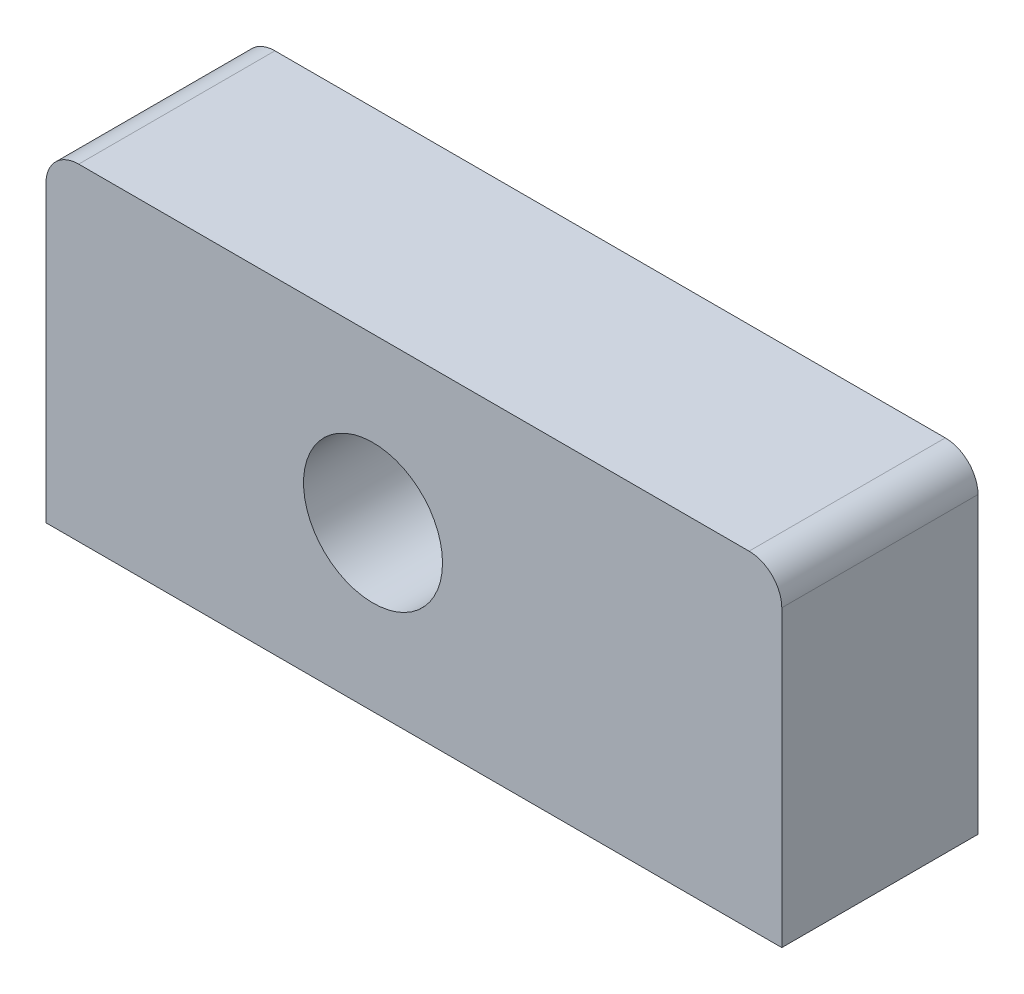
SolidWorks part; units mm, degrees
ref_plane "Front Plane" through (0, 0, 0) normal (0, 0, 1) x (1, 0, 0)
ref_plane "Top Plane" through (0, 0, 0) normal (0, 1, 0) x (1, 0, 0)
ref_plane "Right Plane" through (0, 0, 0) normal (1, 0, 0) x (0, 0, -1)
sketch "Sketch1" plane through (0, 0, 0) normal (0, 0, 1) x (1, 0, 0)
  line L0 (20, 20) -> (20, 0) construction
  line L1 (0, 0) -> (45, 0)
  line L2 (0, 0) -> (0, 20)
  line L3 (0, 20) -> (45, 20)
  line L4 (45, 0) -> (45, 20)
  line L5 (0, 10) -> (45, 10) construction
  circle A0 centre (20, 10) radius 4.25
  point P9 (20, 10)
  dimension "D3" = 8.5
  dimension "D1" = 20
  dimension "D2" = 45
  dimension "D4" = 20
extrude "Boss-Extrude1" add sketch "Sketch1" along normal blind 12
fillet "Fillet1" radius 2 2 edges at (45, 20, 6) (0, 20, 6)
sketch "Sketch2" plane through (0, 0, 0) normal (0, -1, 0) x (1, 0, 0)
  line L0 (0, 6) -> (45, 6) construction
  line L1 (0, 12) -> (0, 0) construction
  line L2 (45, 12) -> (45, 0) construction
  line L3 (0, 0) -> (45, 0) construction
  circle A0 centre (5, 6) radius 1.5
  circle A1 centre (35, 6) radius 1.5
  dimension "D2" = 3
  dimension "D1" = 6
  dimension "D3" = 30
  dimension "D4" = 5
extrude "Cut-Extrude1" cut sketch "Sketch2" against normal blind 5
